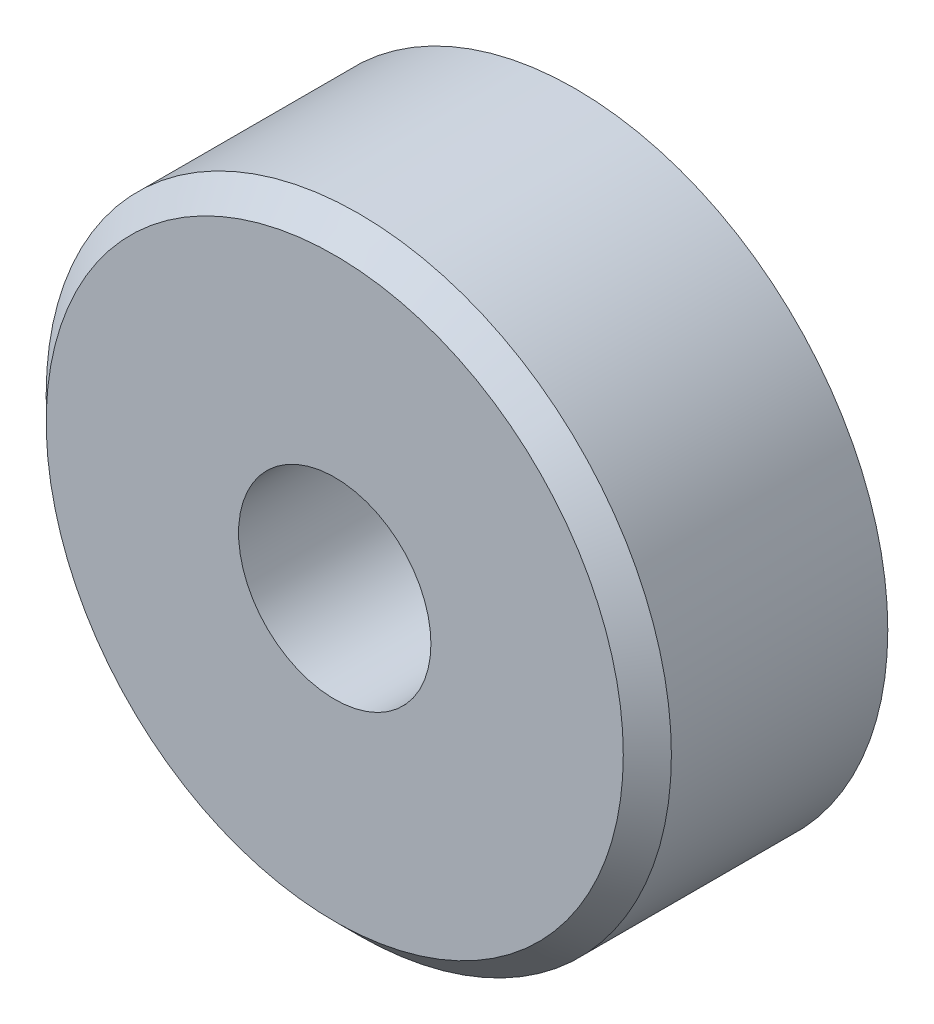
SolidWorks part; units mm, degrees
ref_plane "Front Plane" through (0, 0, 0) normal (0, 0, 1) x (1, 0, 0)
ref_plane "Top Plane" through (0, 0, 0) normal (0, 1, 0) x (1, 0, 0)
ref_plane "Right Plane" through (0, 0, 0) normal (1, 0, 0) x (0, 0, -1)
sketch "Sketch1" plane through (0, 0, 0) normal (0, 0, 1) x (1, 0, 0)
  circle A0 centre (0, 0) radius 3.25
  circle A1 centre (0, 0) radius 1
  dimension "D1" = 6.5
  dimension "D2" = 2
extrude "Boss-Extrude1" add sketch "Sketch1" along normal blind 2.5
chamfer "Chamfer1" distance 0.25 angle 45 1 edges at (3.25, 0, 2.5)
